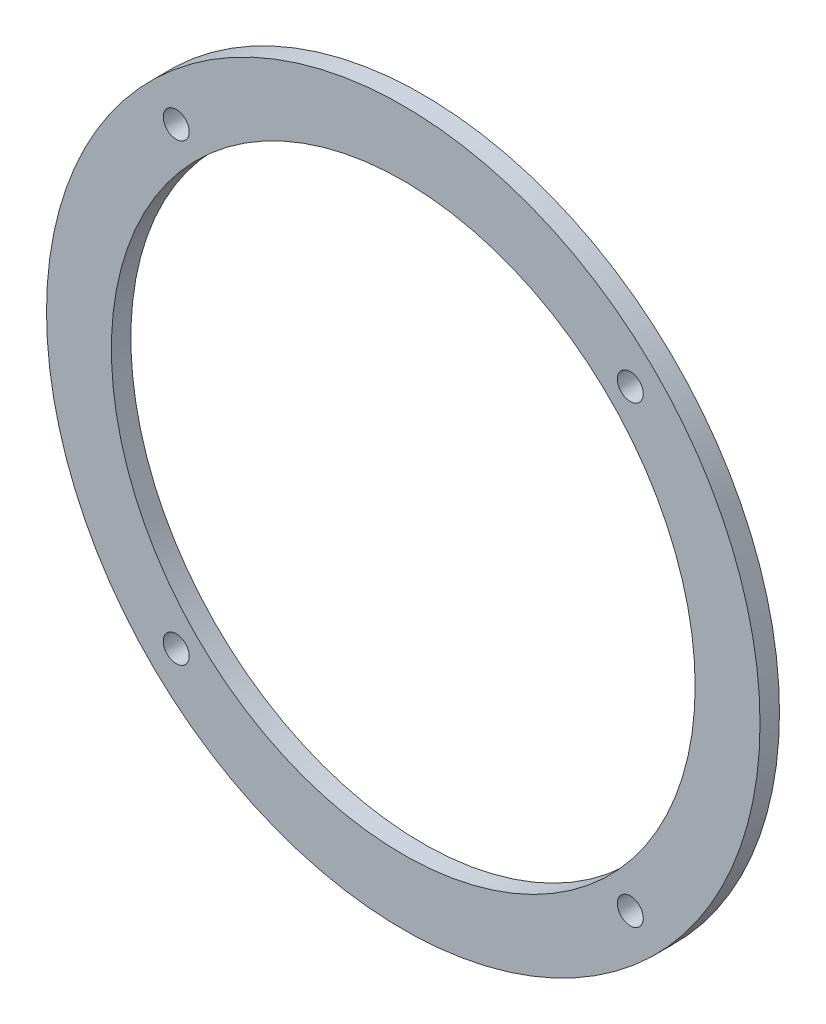
SolidWorks part; units mm, degrees
ref_plane "前视基准面" through (0, 0, 0) normal (0, 0, 1) x (1, 0, 0)
ref_plane "上视基准面" through (0, 0, 0) normal (0, 1, 0) x (1, 0, 0)
ref_plane "右视基准面" through (0, 0, 0) normal (1, 0, 0) x (0, 0, -1)
sketch "草图1" plane through (0, 0, 0) normal (0, 0, 1) x (1, 0, 0)
  line L7 (-35.0018, -35.0018) -> (35.0018, -35.0018)
  line L8 (-35.0018, -35.0018) -> (-35.0018, 35.0018)
  line L9 (-35.0018, 35.0018) -> (35.0018, 35.0018)
  line L10 (35.0018, -35.0018) -> (35.0018, 35.0018)
  line L11 (-35.0018, -35.0018) -> (35.0018, 35.0018) construction
  line L12 (-35.0018, 35.0018) -> (35.0018, -35.0018) construction
  circle A0 centre (0, 0) radius 55
  circle A1 centre (0, 0) radius 45
  circle A2 centre (-35.0018, 35.0018) radius 2
  circle A3 centre (35.0018, 35.0018) radius 2
  circle A4 centre (35.0018, -35.0018) radius 2
  circle A5 centre (-35.0018, -35.0018) radius 2
  dimension "D2" = 90
  dimension "D5" = 4
  dimension "D6" = 4
  dimension "D7" = 4
  dimension "D8" = 4
  dimension "D1" = 110
  dimension "D3" = 99
extrude "凸台-拉伸1" add sketch "草图1" along normal blind 3
